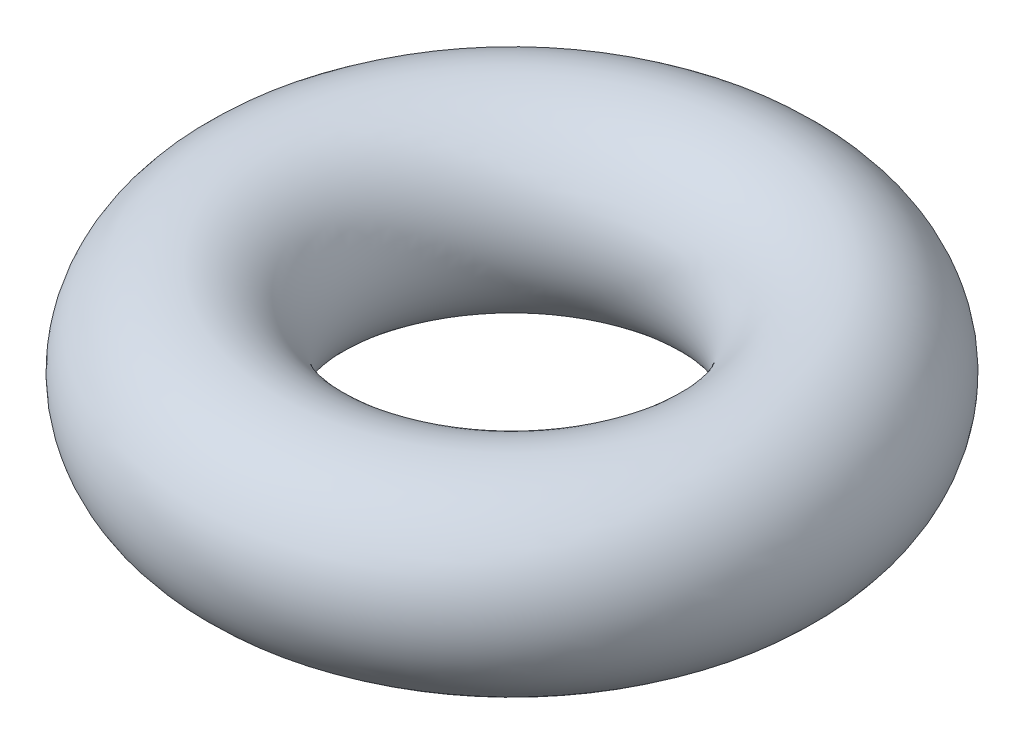
SolidWorks part; units mm, degrees
ref_plane "Front Plane" through (0, 0, 0) normal (0, 0, 1) x (1, 0, 0)
ref_plane "Top Plane" through (0, 0, 0) normal (0, 1, 0) x (1, 0, 0)
ref_plane "Right Plane" through (0, 0, 0) normal (1, 0, 0) x (0, 0, -1)
sketch "Sketch1" plane through (0, 0, 0) normal (0, 0, 1) x (1, 0, 0)
  line L0 (0, 4.8543) -> (0, -4.4753) construction
  circle A0 centre (2.5, 0) radius 1
  point P5 (1.5, 0)
  point P6 (3.5, 0)
  dimension "D1" = 3
  dimension "D2" = 7
revolve "Revolve1" add sketch "Sketch1" angle 360 about L0
